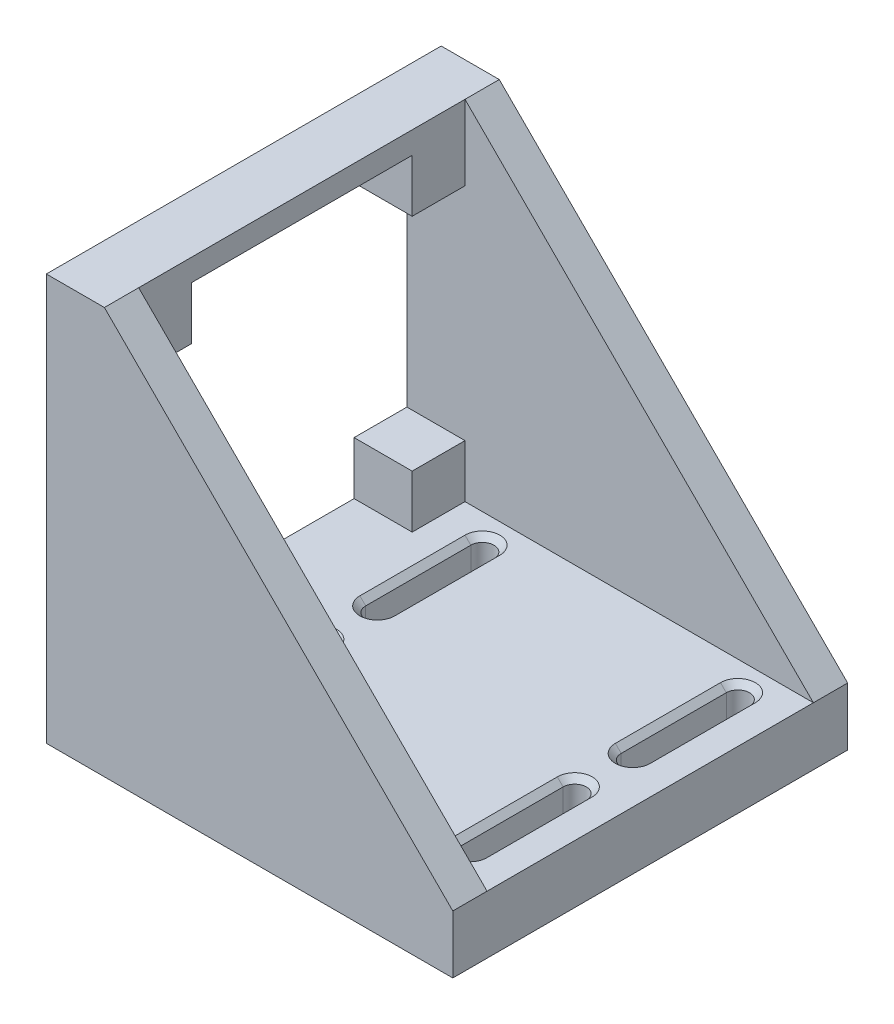
SolidWorks part; units mm, degrees
ref_plane "Front Plane" through (0, 0, 0) normal (0, 0, 1) x (1, 0, 0)
ref_plane "Top Plane" through (0, 0, 0) normal (0, 1, 0) x (1, 0, 0)
ref_plane "Right Plane" through (0, 0, 0) normal (1, 0, 0) x (0, 0, -1)
sketch "Sketch2" plane through (0, 0, 0) normal (0, 0, 1) x (1, 0, 0)
  line L0 (0, 31.9) -> (0, -38.1)
  line L1 (0, -38.1) -> (70, -38.1)
  line L2 (70, -38.1) -> (70, -28.1)
  line L3 (70, -28.1) -> (10, 31.9)
  line L4 (10, 31.9) -> (0, 31.9)
  dimension "D1" = 60
  dimension "D2" = 28.1
  dimension "D3" = 10
extrude "Boss-Extrude1" add sketch "Sketch2" along normal mid plane 68
sketch "Sketch4" plane through (0, 0, 0) normal (0, 0, 1) x (1, 0, 0)
  line L0 (10, 31.9) -> (70, -28.1)
  line L1 (70, -28.1) -> (10, -28.1)
  line L2 (10, -28.1) -> (10, 31.9)
extrude "Cut-Extrude1" cut sketch "Sketch4" against normal mid plane 56.2
sketch "Sketch5" plane through (0, -28.1, 0) normal (0, 1, 0) x (1, 0, 0)
  line L0 (18, 23.1) -> (18, 5) construction
  line L1 (20, 23.1) -> (20, 5)
  line L2 (16, 23.1) -> (16, 5)
  line L3 (62, 23.1) -> (62, 5) construction
  line L4 (64, 23.1) -> (64, 5)
  line L5 (60, 23.1) -> (60, 5)
  line L6 (10, 28.1) -> (10, -28.1) construction
  line L7 (70, 28.1) -> (70, -28.1) construction
  line L8 (10, 28.1) -> (70, 28.1) construction
  line L9 (-55, 0) -> (55, 0) construction
  line L10 (62, -23.1) -> (62, -5) construction
  line L11 (64, -23.1) -> (64, -5)
  line L12 (60, -23.1) -> (60, -5)
  line L13 (18, -23.1) -> (18, -5) construction
  line L14 (20, -23.1) -> (20, -5)
  line L15 (16, -23.1) -> (16, -5)
  arc A0 (20, 23.1) -> (16, 23.1) centre (18, 23.1) ccw
  arc A1 (16, 5) -> (20, 5) centre (18, 5) ccw
  arc A2 (64, 23.1) -> (60, 23.1) centre (62, 23.1) ccw
  arc A3 (60, 5) -> (64, 5) centre (62, 5) ccw
  arc A4 (64, -23.1) -> (60, -23.1) centre (62, -23.1) cw
  arc A5 (60, -5) -> (64, -5) centre (62, -5) cw
  arc A6 (20, -23.1) -> (16, -23.1) centre (18, -23.1) cw
  arc A7 (16, -5) -> (20, -5) centre (18, -5) cw
  point P2 (18, 14.05)
  point P7 (62, 14.05)
  point P21 (0, 0)
  point P26 (62, -14.05)
  point P33 (18, -14.05)
  dimension "D1" = 2
  dimension "D2" = 8
  dimension "D3" = 8
  dimension "D4" = 5
  dimension "D5" = 5
extrude "Cut-Extrude2" cut sketch "Sketch5" against normal through all
chamfer "Chamfer1" distance 1 angle 45 16 edges at (20, -28.1, 14.05) (18, -28.1, 3) (18, -28.1, 25.1) (16, -28.1, 14.05) (64, -28.1, 14.05) (62, -28.1, 3) (62, -28.1, 25.1) (60, -28.1, 14.05) (64, -28.1, -14.05) (62, -28.1, -25.1) (62, -28.1, -3) (60, -28.1, -14.05) (20, -28.1, -14.05) (18, -28.1, -25.1) (18, -28.1, -3) (16, -28.1, -14.05)
sketch "Sketch6" plane through (10, 0, 0) normal (1, 0, 0) x (0, 0, -1)
  line L0 (-28.1, 19) -> (-28.1, -19)
  line L1 (-23.5, -23.5) -> (23.5, -23.5) construction
  line L2 (-23.5, -23.5) -> (-23.5, 23.5) construction
  line L3 (-23.5, 23.5) -> (23.5, 23.5) construction
  line L4 (23.5, -23.5) -> (23.5, 23.5) construction
  line L5 (-23.5, -23.5) -> (23.5, 23.5) construction
  line L6 (-23.5, 23.5) -> (23.5, -23.5) construction
  line L7 (-28.1, -19) -> (-19, -19)
  line L8 (-28.1, 19) -> (-19, 19)
  line L9 (-28.1, 31.9) -> (-28.1, -28.1) construction
  line L10 (-19, 28.1) -> (-19, 19)
  line L11 (19, 28.1) -> (-19, 28.1)
  line L12 (19, 28.1) -> (19, 19)
  line L13 (28.1, 19) -> (19, 19)
  line L14 (28.1, -19) -> (28.1, 19)
  line L15 (28.1, -19) -> (19, -19)
  line L16 (19, -28.1) -> (19, -19)
  line L17 (-19, -28.1) -> (19, -28.1)
  line L18 (-19, -28.1) -> (-19, -19)
  point P0 (2.3191, -5.1912)
  point P13 (-28.1, 0)
  point P29 (0, 0)
  dimension "D1" = 47
  dimension "D2" = 38
  dimension "D4" = 4
extrude "Cut-Extrude3" cut sketch "Sketch6" against normal through all
